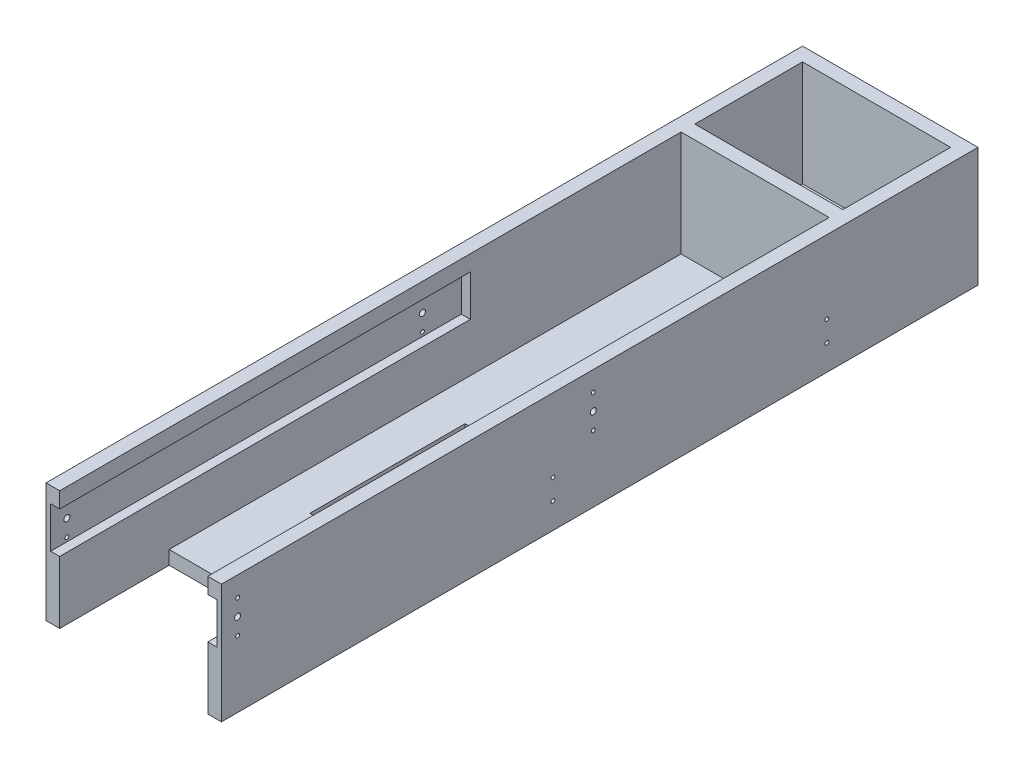
SolidWorks part; units mm, degrees
ref_plane "Front Plane" through (0, 0, 0) normal (0, 0, 1) x (1, 0, 0)
ref_plane "Top Plane" through (0, 0, 0) normal (0, 1, 0) x (1, 0, 0)
ref_plane "Right Plane" through (0, 0, 0) normal (1, 0, 0) x (0, 0, -1)
sketch "Sketch1" plane through (0, 0, 0) normal (0, 0, 1) x (1, 0, 0)
  line L0 (0, 0) -> (34.35, 0)
  line L1 (34.35, 0) -> (34.35, 48)
  line L2 (34.35, 48) -> (40.7, 48)
  line L3 (40.7, 48) -> (40.7, -6.35)
  line L4 (40.7, -6.35) -> (0, -6.35)
  line L5 (0, -6.35) -> (0, 0)
  dimension "D1" = 6.35
  dimension "D2" = 6.35
  dimension "D3" = 34.35
  dimension "D4" = 48
extrude "Boss-Extrude1" add sketch "Sketch1" along normal blind 294.64
mirror "Mirror1" about plane through (0, -6.35, 294.64) normal (1, 0, 0) of bodies 101
sketch "Sketch2" plane through (0, -6.35, 0) normal (0, -1, 0) x (1, 0, 0)
  line L1 (-16.27, 264.16) -> (-21.35, 264.16)
  line L2 (-16.27, 264.16) -> (-16.27, 269.24)
  line L3 (-16.27, 269.24) -> (-21.35, 269.24)
  line L4 (-21.35, 264.16) -> (-21.35, 269.24)
  line L5 (-40.7, 294.64) -> (40.7, 294.64) construction
  line L6 (-40.7, 294.64) -> (-40.7, 0) construction
  line L7 (40.7, 294.64) -> (40.7, 0) construction
  line L8 (33.35, 269.24) -> (28.27, 269.24)
  line L9 (33.35, 269.24) -> (33.35, 264.16)
  line L10 (33.35, 264.16) -> (28.27, 264.16)
  line L11 (28.27, 269.24) -> (28.27, 264.16)
  line L12 (-21.35, 269.24) -> (-16.27, 264.16) construction
  line L13 (-12.46, 254) -> (-25.16, 254)
  line L14 (-12.46, 254) -> (-12.46, 279.4)
  line L15 (-12.46, 279.4) -> (-25.16, 279.4)
  line L16 (-25.16, 254) -> (-25.16, 279.4)
  line L17 (-12.46, 254) -> (-25.16, 279.4) construction
  line L18 (-12.46, 279.4) -> (-25.16, 254) construction
  line L19 (-16.27, 269.24) -> (-21.35, 264.16) construction
  line L20 (-18.81, 257.175) -> (-18.81, 266.7) construction
  line L21 (-18.81, 266.7) -> (-18.81, 276.225) construction
  line L22 (28.27, 269.24) -> (33.35, 264.16) construction
  line L23 (33.35, 269.24) -> (28.27, 264.16) construction
  line L24 (30.81, 257.175) -> (30.81, 266.7) construction
  line L25 (37.16, 279.4) -> (24.46, 279.4)
  line L26 (37.16, 279.4) -> (37.16, 254)
  line L27 (37.16, 254) -> (24.46, 254)
  line L28 (24.46, 279.4) -> (24.46, 254)
  line L29 (37.16, 279.4) -> (24.46, 254) construction
  line L30 (37.16, 254) -> (24.46, 279.4) construction
  line L31 (30.81, 266.7) -> (30.81, 276.225) construction
  circle A0 centre (-18.81, 276.225) radius 1.3891
  circle A1 centre (-18.81, 257.175) radius 1.3891
  circle A2 centre (30.81, 276.225) radius 1.3891
  circle A3 centre (30.81, 257.175) radius 1.3891
  point P14 (-18.81, 266.7)
  point P20 (-18.81, 266.7)
  point P24 (30.81, 266.7)
  dimension "D11" = 2.7781
  dimension "D16" = 2.7781
  dimension "D1" = 5.08
  dimension "D2" = 5.08
  dimension "D3" = 25.4
  dimension "D4" = 19.35
  dimension "D5" = 5.08
  dimension "D6" = 5.08
  dimension "D7" = 25.4
  dimension "D8" = 7.35
  dimension "D9" = 12.7
  dimension "D10" = 25.4
  dimension "D12" = 3.175
  dimension "D13" = 3.175
  dimension "D14" = 12.7
  dimension "D15" = 25.4
  dimension "D17" = 3.175
  dimension "D18" = 3.175
extrude "Cut-Extrude1" [suppressed] cut sketch "Sketch2" against normal up to next contours L10 L11 L8 L9 | L1 L4 L3 L2 | A2 | A3 | A1 | A0
sketch "Sketch3" plane through (0, 0, 0) normal (0, 1, 0) x (1, 0, 0)
  line L0 (-34.35, -294.64) -> (-34.35, 0) construction
  line L1 (34.35, 0) -> (-34.35, 0)
  line L2 (34.35, 0) -> (34.35, -6.35)
  line L3 (34.35, -6.35) -> (-34.35, -6.35)
  line L4 (-34.35, 0) -> (-34.35, -6.35)
  dimension "D1" = 6.35
extrude "Boss-Extrude2" add sketch "Sketch3" along normal up to surface (48 mm away) up to face at (37.525, 48, 147.32)
sketch "Sketch4" plane through (0, -6.35, 0) normal (0, -1, 0) x (1, 0, 0)
  line L0 (0, 12.7) -> (0, 95.2) construction
  line L1 (0, 12.7) -> (0, 0) construction
  line L2 (-34.35, 294.64) -> (-34.35, 6.35) construction
  line L6 (-16.2622, 196.64) -> (9.7378, 196.64)
  line L7 (-16.2622, 196.64) -> (-16.2622, 124.64)
  line L8 (-16.2622, 124.64) -> (9.7378, 124.64)
  line L9 (9.7378, 196.64) -> (9.7378, 124.64)
  line L11 (-40.7, 294.64) -> (40.7, 294.64) construction
  circle A0 centre (0, 12.7) radius 1.3891
  circle A1 centre (0, 95.2) radius 1.3891
  circle A2 centre (0, 53.95) radius 11
  point P8 (-3.2622, 196.64)
  point P26 (0, 53.95)
  dimension "D1" = 2.7781
  dimension "D4" = 22
  dimension "D5" = 31.0878
  dimension "D2" = 82.5
  dimension "D3" = 12.7
  dimension "D8" = 26
  dimension "D9" = 72
  dimension "D11" = 170
extrude "Cut-Extrude2" cut sketch "Sketch4" against normal up to next
sketch "Sketch5" plane through (0, 0, 0) normal (0, 1, 0) x (1, 0, 0)
  line L0 (16.0628, -139.74) -> (16.0628, -195.74) construction
  line L2 (9.7378, -196.64) -> (9.7378, -124.64) construction
  circle A0 centre (16.0628, -195.74) radius 1.7859
  circle A1 centre (16.0628, -139.74) radius 1.7859
  dimension "D2" = 3.5719
  dimension "D1" = 6.325
  dimension "D3" = 56
  dimension "D4" = 15.1
extrude "Cut-Extrude3" cut sketch "Sketch5" against normal up to next
sketch "Sketch6" plane through (-34.35, 0, 0) normal (1, 0, 0) x (0, 0, -1)
  line L0 (-287.14, 32.15) -> (-122.14, 32.15) construction
  line L1 (-294.64, 48) -> (-6.35, 48) construction
  line L2 (-294.64, 48) -> (-294.64, 0) construction
  circle A0 centre (-287.14, 32.15) radius 1.3891
  circle A1 centre (-122.14, 32.15) radius 1.3891
  dimension "D2" = 2.7781
  dimension "D1" = 15.85
  dimension "D3" = 7.5
  dimension "D4" = 165
extrude "Cut-Extrude4" cut sketch "Sketch6" along normal up to surface and the other way up to surface up to face at (40.7, 20.825, 147.32) other way up to face at (-40.7, 20.825, 147.32)
sketch "Sketch7" plane through (-40.7, 0, 0) normal (-1, 0, 0) x (0, 0, 1)
  line B0 (0, 48) -> (0, -6.35)
  line B1 (0, -6.35) -> (294.64, -6.35)
  line B2 (294.64, -6.35) -> (294.64, 48)
  line B3 (294.64, 48) -> (0, 48)
  circle B4 centre (84.24, 27.9) radius 1.1906
  circle B5 centre (284.64, 27.9) radius 1.1906
sketch_block_instance "Block1-1"
sketch_block "Block1"
sketch "Sketch8" plane through (40.7, 0, 0) normal (1, 0, 0) x (0, 0, -1)
  line B0 (0, -6.35) -> (0, 48)
  line B1 (0, 48) -> (-294.64, 48)
  line B2 (-294.64, 48) -> (-294.64, -6.35)
  line B3 (-294.64, -6.35) -> (0, -6.35)
sketch_block_instance "Block2-1"
sketch_block "Block2"
sketch "Sketch9" plane through (0, 0, 6.35) normal (0, 0, 1) x (1, 0, 0)
  line B0 (33.35, 0) -> (33.35, 48)
  line B1 (33.35, 48) -> (-33.35, 48)
  line B2 (-33.35, 48) -> (-33.35, 0)
  line B3 (-33.35, 0) -> (33.35, 0)
sketch_block_instance "Block3-1"
sketch_block "Block3"
sketch "Sketch10" plane through (0, 0, 0) normal (0, 1, 0) x (1, 0, 0)
  line B0 (33.35, -6.35) -> (-33.35, -6.35)
  line B1 (-33.35, -6.35) -> (-33.35, -294.64)
  line B2 (-33.35, -294.64) -> (33.35, -294.64)
  line B3 (33.35, -294.64) -> (33.35, -6.35)
  line B4 (27.27, -269.24) -> (32.35, -269.24)
  line B5 (32.35, -264.16) -> (32.35, -269.24)
  line B6 (27.27, -264.16) -> (27.27, -269.24)
  line B7 (27.27, -264.16) -> (32.35, -264.16)
  line B8 (-20.35, -269.24) -> (-20.35, -264.16)
  line B9 (-20.35, -264.16) -> (-15.27, -264.16)
  line B10 (-15.27, -269.24) -> (-15.27, -264.16)
  line B11 (-20.35, -269.24) -> (-15.27, -269.24)
  line B12 (-9.3, -124.64) -> (-9.3, -196.64)
  line B13 (-9.3, -196.64) -> (16.7, -196.64)
  line B14 (16.7, -196.64) -> (16.7, -124.64)
  line B15 (16.7, -124.64) -> (-9.3, -124.64)
  circle B16 centre (29.81, -276.225) radius 1.3891
  circle B17 centre (29.81, -257.175) radius 1.3891
  circle B18 centre (-17.81, -257.175) radius 1.3891
  circle B19 centre (-17.81, -276.225) radius 1.3891
  circle B20 centre (22.325, -139.74) radius 1.7859
  circle B21 centre (22.325, -195.74) radius 1.7859
  circle B22 centre (0, -95.2) radius 2.54
  circle B23 centre (0, -53.95) radius 12.7
  circle B24 centre (0, -12.7) radius 2.54
sketch_block_instance "Block4-1"
sketch_block "Block4"
sketch "Sketch11" plane through (34.35, 0, 0) normal (-1, 0, 0) x (0, 0, 1)
  line L0 (13.75, 5.5) -> (13.75, 15) construction
  line L1 (294.64, 0) -> (6.35, 0) construction
  line L2 (6.35, 48) -> (6.35, 0) construction
  line L3 (140.81, 5.5) -> (140.81, 15) construction
  circle A0 centre (13.75, 5.5) radius 0.889
  circle A1 centre (13.75, 15) radius 0.889
  circle A2 centre (140.81, 15) radius 0.889
  circle A3 centre (140.81, 5.5) radius 0.889
  dimension "D1" = 1.778
  dimension "D2" = 9.5
  dimension "D3" = 5.5
  dimension "D4" = 7.4
  dimension "D5" = 5.5
  dimension "D6" = 127.06
extrude "Cut-Extrude5" cut sketch "Sketch11" against normal up to next
sketch "Sketch12" plane through (0, 0, 294.64) normal (0, 0, 1) x (1, 0, 0)
  line L0 (-40.7, -6.35) -> (40.7, -6.35) construction
  line L1 (-34.35, 0) -> (34.35, 0)
  line L2 (-34.35, 0) -> (-34.35, -6.35)
  line L3 (-34.35, -6.35) -> (34.35, -6.35)
  line L4 (34.35, 0) -> (34.35, -6.35)
  line L5 (34.35, 48) -> (34.35, 0) construction
extrude "Cut-Extrude6" cut sketch "Sketch12" against normal blind 50.8
sketch "Sketch13" plane through (0, 0, 0) normal (0, 0, -1) x (-1, 0, 0)
  line L19 (40.7, -6.35) -> (40.7, 48) construction
  line L20 (40.7, -6.35) -> (-40.7, -6.35) construction
  line L21 (-40.7, -6.35) -> (-40.7, 48) construction
  line L22 (34.35, 48) -> (34.35, 0)
  line L23 (34.35, 0) -> (-34.35, 0)
  line L24 (-34.35, 0) -> (-34.35, 48)
  line L25 (34.35, 48) -> (34.35, 0)
  line L26 (34.35, 0) -> (-34.35, 0)
  line L27 (-34.35, 0) -> (-34.35, 48)
  line L28 (40.7, -6.35) -> (40.7, 48)
  line L29 (40.7, -6.35) -> (-40.7, -6.35)
  line L30 (-40.7, -6.35) -> (-40.7, 48)
  line L31 (40.7, 48) -> (34.35, 48)
  line L32 (-34.35, 48) -> (-40.7, 48)
  dimension "D1" = 6.35
extrude "Boss-Extrude3" add sketch "Sketch13" along normal blind 50
sketch "Sketch14" plane through (0, 0, -50) normal (0, 0, -1) x (-1, 0, 0)
  line L1 (-40.7, -6.35) -> (40.7, -6.35)
  line L2 (-40.7, -6.35) -> (-40.7, 48)
  line L3 (-40.7, 48) -> (40.7, 48)
  line L4 (40.7, -6.35) -> (40.7, 48)
extrude "Boss-Extrude4" add sketch "Sketch14" along normal blind 6.35
sketch "Sketch15" plane through (0, 48, 0) normal (0, 1, 0) x (1, 0, 0)
  line L0 (34.35, 50) -> (34.35, 0) construction
  line L1 (-34.35, 50) -> (34.35, 50) construction
  line L2 (-34.35, 50) -> (-34.35, 0) construction
  line L3 (34.35, 0) -> (-34.35, 0) construction
  line L4 (34.35, 50) -> (34.35, 0)
  line L5 (-34.35, 50) -> (34.35, 50)
  line L6 (-34.35, 50) -> (-34.35, 0)
  line L7 (34.35, 0) -> (-34.35, 0)
  line L8 (40.7, -294.64) -> (40.7, 56.35)
  line L9 (40.7, 56.35) -> (-40.7, 56.35)
  line L10 (-40.7, 56.35) -> (-40.7, -294.64)
  line L11 (-40.7, -294.64) -> (-34.35, -294.64)
  line L12 (-34.35, -294.64) -> (-34.35, -6.35)
  line L13 (-34.35, -6.35) -> (34.35, -6.35)
  line L14 (34.35, -6.35) -> (34.35, -294.64)
  line L15 (34.35, -294.64) -> (40.7, -294.64)
  line L16 (40.7, -294.64) -> (40.7, 56.35)
  line L17 (40.7, 56.35) -> (-40.7, 56.35)
  line L18 (-40.7, 56.35) -> (-40.7, -294.64)
  line L19 (-40.7, -294.64) -> (-34.35, -294.64)
  line L20 (-34.35, -294.64) -> (-34.35, -6.35)
  line L21 (-34.35, -6.35) -> (34.35, -6.35)
  line L22 (34.35, -6.35) -> (34.35, -294.64)
  line L23 (34.35, -294.64) -> (40.7, -294.64)
  dimension "D1" = 0
extrude "Boss-Extrude5" add sketch "Sketch15" along normal blind 1
sketch "Left Side" plane through (40.7, 0, 0) normal (1, 0, 0) x (0, 0, -1)
  line L0 (53.175, 42.65) -> (53.175, 6.35) construction
  line L1 (53.175, 6.35) -> (53.175, -3.175) construction
  line L2 (-237.49, -3.175) -> (-92.1575, -3.175) construction
  line L3 (-92.1575, -3.175) -> (53.175, -3.175) construction
  line L4 (-294.64, -6.35) -> (56.35, -6.35)
  line L5 (56.35, -6.35) -> (56.35, 49)
  line L6 (56.35, 49) -> (-294.64, 49)
  line L7 (-294.64, 49) -> (-294.64, -6.35)
  line L8 (-294.64, -6.35) -> (56.35, -6.35)
  line L9 (56.35, -6.35) -> (56.35, 49)
  line L10 (56.35, 49) -> (-294.64, 49)
  line L11 (-294.64, 49) -> (-294.64, -6.35)
  line L12 (-3.175, 42.65) -> (53.175, 42.65) construction
  line L13 (-3.175, 6.35) -> (-3.175, 42.65) construction
  circle A0 centre (-237.49, -3.175) radius 1.7859
  circle A1 centre (-140.81, 5.5) radius 0.889
  circle A2 centre (-140.81, 5.5) radius 0.889
  circle A3 centre (-140.81, 15) radius 0.889
  circle A4 centre (-140.81, 15) radius 0.889
  circle A5 centre (-13.75, 15) radius 0.889
  circle A6 centre (-13.75, 15) radius 0.889
  circle A7 centre (-13.75, 5.5) radius 0.889
  circle A8 centre (-13.75, 5.5) radius 0.889
  circle A9 centre (-287.14, 32.15) radius 1.3891
  circle A10 centre (-287.14, 32.15) radius 1.3891
  circle A11 centre (-122.14, 32.15) radius 1.3891
  circle A12 centre (-122.14, 32.15) radius 1.3891
  circle A13 centre (53.175, -3.175) radius 1.7859
  circle A14 centre (53.175, 42.65) radius 1.7859
  circle A15 centre (53.175, 6.35) radius 1.7859
  circle A16 centre (-92.1575, -3.175) radius 1.7859
  circle A17 centre (-3.175, 42.65) radius 1.7859
  circle A18 centre (-3.175, 6.35) radius 1.7859
  dimension "D9" = 3.5719
  dimension "D12" = 3.5719
  dimension "D8" = 3.175
  dimension "D10" = 57.15
  dimension "D11" = 3.175
  dimension "D13" = 3.175
  dimension "D14" = 12.7
  dimension "D15" = 6.35
  dimension "D16" = 56.35
  dimension "D1" = 0
  dimension "D2" = 0
  dimension "D3" = 0
  dimension "D4" = 0
  dimension "D5" = 0
  dimension "D6" = 0
  dimension "D7" = 0
sketch "Right Side" plane through (-40.7, 0, 0) normal (-1, 0, 0) x (0, 0, 1)
  line L4 (294.64, 49) -> (-56.35, 49)
  line L5 (294.64, -6.35) -> (294.64, 49)
  line L6 (-56.35, -6.35) -> (294.64, -6.35)
  line L7 (-56.35, 49) -> (-56.35, -6.35)
  line L8 (294.64, 49) -> (-56.35, 49)
  line L9 (294.64, -6.35) -> (294.64, 49)
  line L10 (-56.35, -6.35) -> (294.64, -6.35)
  line L11 (-56.35, 49) -> (-56.35, -6.35)
  circle A9 centre (92.1575, -3.175) radius 1.7859
  circle A10 centre (92.1575, -3.175) radius 1.7859
  circle A11 centre (-53.175, 6.35) radius 1.7859
  circle A12 centre (-53.175, 6.35) radius 1.7859
  circle A13 centre (-53.175, 42.65) radius 1.7859
  circle A14 centre (-53.175, 42.65) radius 1.7859
  circle A15 centre (-53.175, -3.175) radius 1.7859
  circle A16 centre (-53.175, -3.175) radius 1.7859
  circle A17 centre (122.14, 32.15) radius 1.3891
  circle A18 centre (122.14, 32.15) radius 1.3891
  circle A19 centre (287.14, 32.15) radius 1.3891
  circle A20 centre (287.14, 32.15) radius 1.3891
  circle A21 centre (237.49, -3.175) radius 1.7859
  circle A22 centre (237.49, -3.175) radius 1.7859
  circle A23 centre (3.175, 6.35) radius 1.7859
  circle A24 centre (3.175, 6.35) radius 1.7859
  circle A25 centre (3.175, 42.65) radius 1.7859
  circle A26 centre (3.175, 42.65) radius 1.7859
  dimension "D5" = 0
  dimension "D6" = 0
  dimension "D7" = 0
  dimension "D8" = 0
  dimension "D9" = 0
  dimension "D10" = 0
  dimension "D11" = 0
  dimension "D12" = 0
  dimension "D13" = 0
  dimension "D14" = 0
sketch "Bottom" plane through (0, 0, 0) normal (0, 1, 0) x (1, 0, 0)
  line L0 (-16.2622, -196.64) -> (9.7378, -196.64) construction
  line L1 (-16.2622, -124.64) -> (-16.2622, -196.64) construction
  line L2 (9.7378, -196.64) -> (9.7378, -124.64) construction
  line L3 (9.7378, -124.64) -> (-16.2622, -124.64) construction
  line L4 (-16.2622, -196.64) -> (9.7378, -196.64)
  line L5 (-16.2622, -124.64) -> (-16.2622, -196.64)
  line L6 (9.7378, -196.64) -> (9.7378, -124.64)
  line L7 (9.7378, -124.64) -> (-16.2622, -124.64)
  line L9 (34.35, -243.84) -> (-34.35, -243.84)
  line L10 (34.35, -243.84) -> (34.35, 50)
  line L11 (34.35, 50) -> (-34.35, 50)
  line L12 (-34.35, -243.84) -> (-34.35, 50)
  circle A0 centre (16.0628, -139.74) radius 1.7859 construction
  circle A1 centre (16.0628, -195.74) radius 1.7859 construction
  circle A2 centre (0, -95.2) radius 1.3891 construction
  circle A3 centre (0, -53.95) radius 11 construction
  circle A4 centre (0, -12.7) radius 1.3891 construction
  circle A5 centre (16.0628, -139.74) radius 1.7859
  circle A6 centre (16.0628, -195.74) radius 1.7859
  circle A7 centre (0, -95.2) radius 1.3891
  circle A8 centre (0, -53.95) radius 11
  circle A9 centre (0, -12.7) radius 1.3891
sketch "Back" plane through (0, 0, -56.35) normal (0, 0, -1) x (-1, 0, 0)
  line L0 (-34.35, 49) -> (-34.35, -6.35)
  line L1 (34.35, -6.35) -> (34.35, 49)
  line L2 (-40.7, 6.35) -> (-40.7, 42.65) construction
  line L3 (40.7, -6.35) -> (40.7, 49) construction
  line L4 (-40.7, 49) -> (-40.7, -6.35)
  line L5 (-40.7, -6.35) -> (40.7, -6.35)
  line L6 (40.7, -6.35) -> (40.7, 49)
  line L7 (40.7, 49) -> (-40.7, 49)
  line L9 (-34.35, -6.35) -> (34.35, -6.35)
  line L11 (34.35, 49) -> (-34.35, 49)
  line L12 (-34.35, -6.35) -> (34.35, -6.35)
  dimension "D2" = 6.35
  dimension "D3" = 6.35
  dimension "D1" = 0
sketch "Divider" plane through (0, 0, 0) normal (0, 0, -1) x (-1, 0, 0)
  line L4 (-34.35, 49) -> (-34.35, 0)
  line L5 (-34.35, 0) -> (34.35, 0)
  line L6 (34.35, 0) -> (34.35, 49)
  line L7 (34.35, 49) -> (-34.35, 49)
  line L8 (-34.35, 49) -> (-34.35, 0)
  line L9 (-34.35, 0) -> (34.35, 0)
  line L10 (34.35, 0) -> (34.35, 49)
  line L11 (34.35, 49) -> (-34.35, 49)
  dimension "D1" = 0
sketch "Sketch16" plane through (-34.35, 0, 0) normal (1, 0, 0) x (0, 0, -1)
  line L0 (-294.64, 49) -> (-294.64, -6.35) construction
  line L1 (-294.64, 41.675) -> (-104.14, 41.675)
  line L2 (-294.64, 41.675) -> (-294.64, 22.625)
  line L3 (-294.64, 22.625) -> (-104.14, 22.625)
  line L4 (-104.14, 41.675) -> (-104.14, 22.625)
  line L5 (-287.14, 32.15) -> (-294.64, 32.15) construction
  dimension "D1" = 19.05
  dimension "D2" = 190.5
extrude "Cut-Extrude7" cut sketch "Sketch16" against normal blind 4.175
sketch "Sketch17" plane through (34.35, 0, 0) normal (-1, 0, 0) x (0, 0, 1)
  line L0 (294.64, 49) -> (294.64, -6.35) construction
  line L1 (294.64, 41.675) -> (104.14, 41.675)
  line L2 (294.64, 41.675) -> (294.64, 22.625)
  line L3 (294.64, 22.625) -> (104.14, 22.625)
  line L4 (104.14, 41.675) -> (104.14, 22.625)
  line L5 (294.64, 32.15) -> (287.14, 32.15) construction
  dimension "D1" = 19.05
  dimension "D2" = 190.5
extrude "Cut-Extrude8" cut sketch "Sketch17" against normal blind 4.175
sketch "Sketch18" plane through (-38.525, 0, 0) normal (1, 0, 0) x (0, 0, -1)
  line L0 (-287.14, 39.77) -> (-287.14, 32.15) construction
  line L1 (-287.14, 32.15) -> (-287.14, 24.53) construction
  line L2 (-122.14, 24.53) -> (-122.14, 32.15) construction
  line L3 (-122.14, 32.15) -> (-122.14, 39.77) construction
  circle A0 centre (-287.14, 39.77) radius 0.889
  circle A1 centre (-287.14, 24.53) radius 0.889
  circle A2 centre (-122.14, 39.77) radius 0.889
  circle A3 centre (-122.14, 24.53) radius 0.889
  dimension "D1" = 1.778
  dimension "D2" = 7.62
extrude "Cut-Extrude9" cut sketch "Sketch18" against normal through all both and the other way through all
